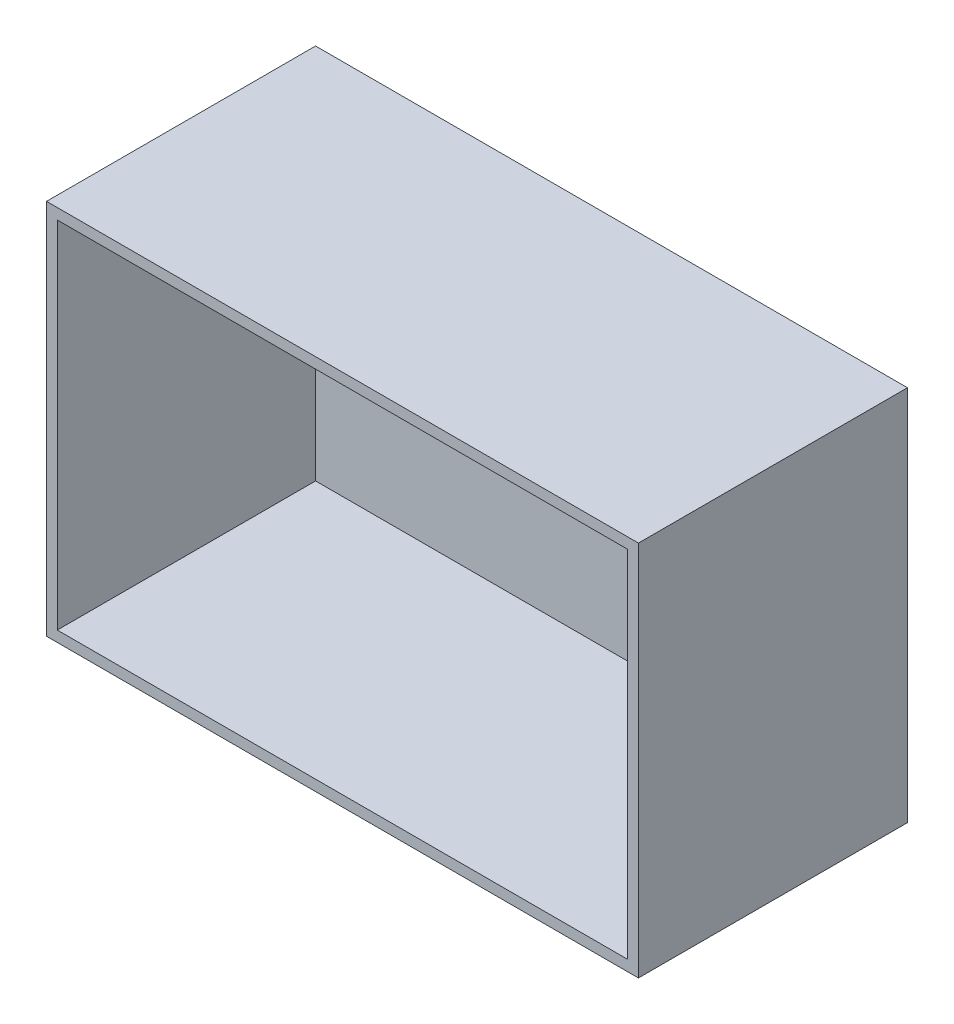
SolidWorks part; units mm, degrees
ref_plane "Front Plane" through (0, 0, 0) normal (0, 0, 1) x (1, 0, 0)
ref_plane "Top Plane" through (0, 0, 0) normal (0, 1, 0) x (1, 0, 0)
ref_plane "Right Plane" through (0, 0, 0) normal (1, 0, 0) x (0, 0, -1)
sketch "Sketch1" plane through (0, 0, 0) normal (0, 0, 1) x (1, 0, 0)
  line L1 (-58.2887, 24.8786) -> (81.4113, 24.8786)
  line L2 (-58.2887, 24.8786) -> (-58.2887, -64.0214)
  line L3 (-58.2887, -64.0214) -> (81.4113, -64.0214)
  line L4 (81.4113, 24.8786) -> (81.4113, -64.0214)
  dimension "D1" = 139.7
  dimension "D2" = 88.9
extrude "Boss-Extrude1" add sketch "Sketch1" along normal blind 63.5
shell "Shell1" thickness 2.54
sketch "Sketch2" plane through (0, 0, 0) normal (0, 0, -1) x (-1, 0, 0)
  line L0 (-81.4113, -64.0214) -> (-81.4113, 24.8786) construction
  circle A0 centre (-40.7713, -20.3173) radius 7.62
  dimension "D2" = 15.24
  dimension "D1" = 40.64
extrude "Cut-Extrude1" cut sketch "Sketch2" against normal blind 76.2
